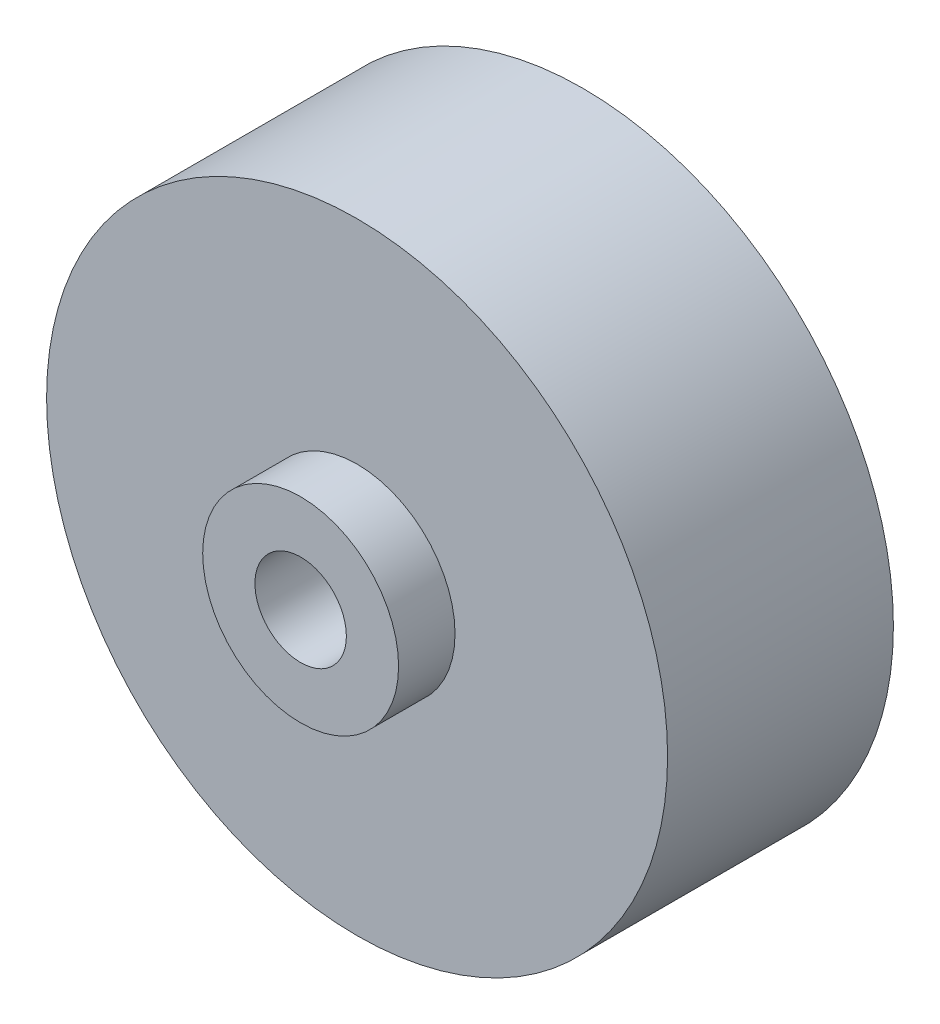
SolidWorks part; units mm, degrees
ref_plane "Alzado" through (0, 0, 0) normal (0, 0, 1) x (1, 0, 0)
ref_plane "Planta" through (0, 0, 0) normal (0, 1, 0) x (1, 0, 0)
ref_plane "Vista lateral" through (0, 0, 0) normal (1, 0, 0) x (0, 0, -1)
sketch "Croquis1" plane through (0, 0, 0) normal (0, 0, 1) x (1, 0, 0)
  circle A0 centre (0, 0) radius 27.5
  dimension "D1" = 55
extrude "Saliente-Extruir1" add sketch "Croquis1" along normal mid plane 20
sketch "Croquis4" plane through (0, 0, 10) normal (0, 0, 1) x (1, 0, 0)
  circle A0 centre (0, 0) radius 4.05
  dimension "D1" = 8.1
extrude "Cortar-Extruir2" cut sketch "Croquis4" against normal blind 108
sketch "Croquis5" plane through (0, 0, 10) normal (0, 0, 1) x (1, 0, 0)
  circle A0 centre (0, 0) radius 8.675
  dimension "D1" = 17.35
extrude "Saliente-Extruir2" add sketch "Croquis5" along normal blind 5
sketch "Croquis6" plane through (0, 0, 15) normal (0, 0, 1) x (1, 0, 0)
  circle A0 centre (0, 0) radius 4.05
  dimension "D1" = 8.1
extrude "Cortar-Extruir3" cut sketch "Croquis6" against normal mid plane 244
